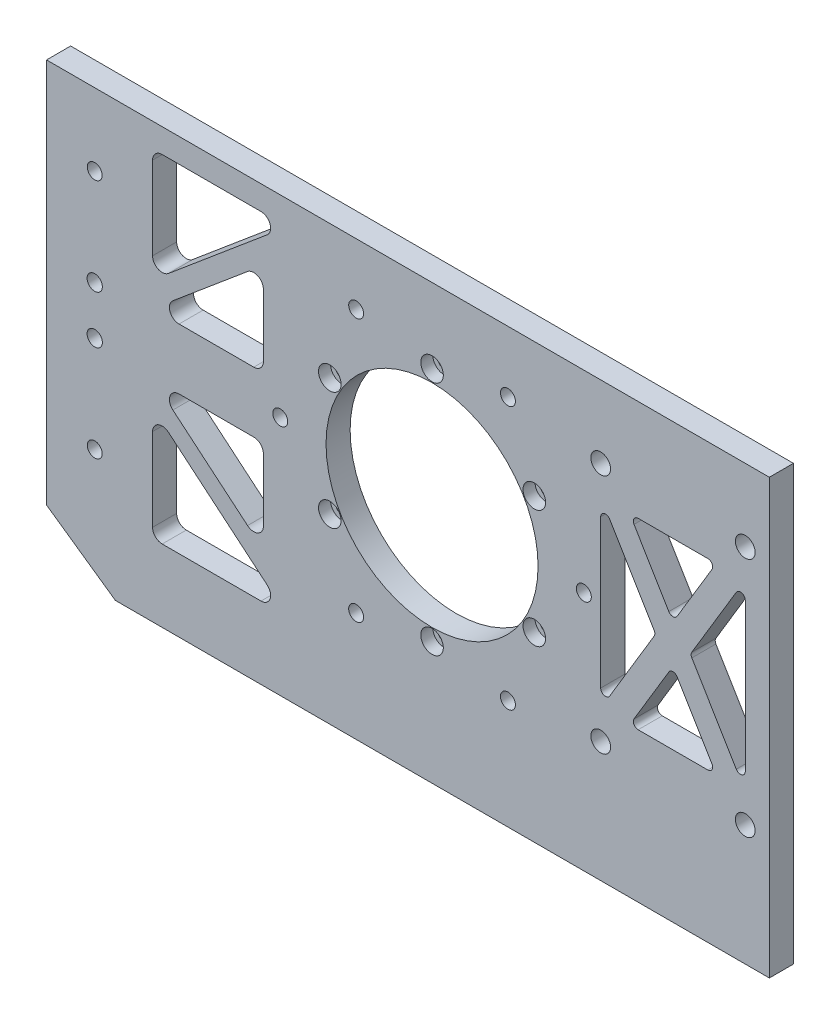
SolidWorks part; units mm, degrees
ref_plane "前视基准面" through (0, 0, 0) normal (0, 0, 1) x (1, 0, 0)
ref_plane "上视基准面" through (0, 0, 0) normal (0, 1, 0) x (1, 0, 0)
ref_plane "右视基准面" through (0, 0, 0) normal (1, 0, 0) x (0, 0, -1)
sketch "草图1" plane through (0, 0, 0) normal (0, 0, 1) x (1, 0, 0)
  line L1 (-80, 40) -> (70, 40)
  line L2 (-80, 40) -> (-80, -40)
  line L3 (-80, -40) -> (70, -40)
  line L4 (70, 40) -> (70, -40)
  circle A0 centre (0, 0) radius 24.5 construction
  circle A1 centre (0, -24.5) radius 1.3
  circle A2 centre (-21.2176, -12.25) radius 1.3
  circle A3 centre (-21.2176, 12.25) radius 1.3
  circle A4 centre (0, 0) radius 22
  circle A5 centre (0, 24.5) radius 1.3
  circle A6 centre (21.2176, 12.25) radius 1.3
  circle A7 centre (21.2176, -12.25) radius 1.3
  point P11 (0, 0)
  point P15 (70, 0)
  dimension "D1" = 49
  dimension "D2" = 2.6
  dimension "D4" = 44
  dimension "D5" = 80
  dimension "D6" = 70
  dimension "D7" = 80
  dimension "D3" = 6
extrude "凸台-拉伸1" add sketch "草图1" along normal blind 5
sketch "草图2" plane through (0, 0, 5) normal (0, 0, 1) x (1, 0, 0)
  circle A0 centre (-21.2176, 12.25) radius 2.34
  circle A1 centre (0, 24.5) radius 2.34
  circle A2 centre (21.2176, 12.25) radius 2.34
  circle A3 centre (21.2176, -12.25) radius 2.34
  circle A4 centre (0, -24.5) radius 2.34
  circle A5 centre (-21.2176, -12.25) radius 2.34
  point P15 (0, 0)
  dimension "D1" = 4.68
  dimension "D2" = 6
extrude "切除-拉伸1" cut sketch "草图2" against normal blind 2.5
sketch "草图3" plane through (0, 0, 5) normal (0, 0, 1) x (1, 0, 0)
  line L0 (0, 0) -> (-70, 0) construction
  line L1 (-70, 0) -> (-70, -25) construction
  line L3 (-70, 0) -> (-70, 24.3133)
  circle A4 centre (-70, -25) radius 1.55
  circle A5 centre (-70, -5) radius 1.5828
  circle A6 centre (-70, 25) radius 1.55
  circle A7 centre (-70, 5) radius 1.5828
  point P6 (-70, 0)
  dimension "D3" = 3.1
  dimension "D4" = 20
  dimension "D1" = 70
  dimension "D2" = 25
extrude "切除-拉伸3" cut sketch "草图3" against normal blind 12.5
sketch "草图4" plane through (0, 0, 5) normal (0, 0, 1) x (1, 0, 0)
  line L0 (-58, 35) -> (-30, 35)
  line L1 (-30, 35) -> (-58, 11.5052)
  line L2 (-58, 11.5052) -> (-58, 35)
  line L3 (-35, 25.5829) -> (-58, 6.2836)
  line L4 (-58, 6.2836) -> (-35, 6.2836)
  line L5 (-35, 6.2836) -> (-35, 25.5829)
  line L8 (70, 40) -> (-80, 40) construction
  line L9 (-80, 40) -> (-80, -40) construction
  dimension "D1" = 5
  dimension "D2" = 22
  dimension "D3" = 140
  dimension "D4" = 45
  dimension "D6" = 4
extrude "切除-拉伸5" cut sketch "草图4" against normal blind 8 contours L2 L0 L1 | L5 L3 L4
fillet "圆角3" radius 2 6 edges at (-35, 6.2836, 2.5) (-58, 6.2836, 2.5) (-35, 25.5829, 2.5) (-30, 35, 2.5) (-58, 11.5052, 2.5) (-58, 35, 2.5)
mirror "镜向2" about plane through (0, 0, 0) normal (0, 1, 0) of "圆角3", "切除-拉伸5"
sketch "草图10" plane through (0, 0, 5) normal (0, 0, 1) x (1, 0, 0)
  line L0 (-80, -40) -> (-127.0531, -7.0531)
  line L1 (-127.0531, -7.0531) -> (-80, 40)
  line L2 (-80, -40) -> (70, -40) construction
  line L3 (-80, 40) -> (-80, -40) construction
  line L4 (-80, 40) -> (-80, -40)
  dimension "D1" = 145
  dimension "D2" = 45
extrude "凸台-拉伸4" add sketch "草图10" against normal up to surface (5 mm away) contours L4 L0 L1 up to face at (-49.3474, 27.3903, 0)
fillet "圆角5" radius 5 1 edges at (-127.0531, -7.0531, 2.5)
sketch "草图11" plane through (0, 0, 5) normal (0, 0, 1) x (1, 0, 0)
  line L0 (0, 0) -> (0, 34) construction
  line L1 (0, 0) -> (-15.75, 27.2798)
  circle A0 centre (0, 0) radius 29 construction
  circle A1 centre (0, 0) radius 34 construction
  circle A2 centre (0, 0) radius 31.5 construction
  circle A3 centre (-15.75, 27.2798) radius 1.55
  circle A4 centre (15.75, 27.2798) radius 1.55
  circle A5 centre (31.5, 0) radius 1.55
  circle A6 centre (15.75, -27.2798) radius 1.55
  circle A7 centre (-15.75, -27.2798) radius 1.55
  circle A8 centre (-31.5, 0) radius 1.55
  point P20 (0, 0)
  dimension "D1" = 58
  dimension "D2" = 68
  dimension "D3" = 63
  dimension "D5" = 3.1
  dimension "D4" = 30
  dimension "D6" = 6
extrude "切除-拉伸7" cut sketch "草图11" against normal blind 25 contours A3 | A4 | A5 | A6 | A7 | A8
sketch "草图12" plane through (0, 0, 5) normal (0, 0, 1) x (1, 0, 0)
  line L0 (0, 0) -> (50, 0) construction
  line L6 (35, -25) -> (65, -25) construction
  line L7 (35, -25) -> (35, 25) construction
  line L8 (35, 25) -> (65, 25) construction
  line L9 (65, -25) -> (65, 25) construction
  line L10 (35, -25) -> (65, 25) construction
  line L11 (35, 25) -> (65, -25) construction
  circle A0 centre (0, 0) radius 28 construction
  circle A1 centre (35, 25) radius 2.05
  circle A2 centre (65, 25) radius 2.05
  circle A3 centre (65, -25) radius 2.05
  circle A4 centre (35, -25) radius 2.05
  dimension "D3" = 56
  dimension "D5" = 4.1
  dimension "D6" = 4.1
  dimension "D1" = 30
  dimension "D2" = 50
  dimension "D4" = 50
extrude "切除-拉伸8" cut sketch "草图12" against normal blind 10
sketch "草图13" plane through (0, 0, 5) normal (0, 0, 1) x (1, 0, 0)
  line L0 (35, 25) -> (65, -25) construction
  line L6 (35, 25) -> (65, -25) construction
  line L10 (35, 19) -> (35, -19)
  line L11 (35, -19) -> (46.4, 0)
  line L12 (46.4, 0) -> (35, 19)
  line L13 (35, -25) -> (65, 25) construction
  line L14 (50, 0) -> (50, -49.4768) construction
  line L15 (65, -19) -> (53.6, 0)
  line L16 (65, 19) -> (65, -19)
  line L17 (53.6, 0) -> (65, 19)
  line L18 (41, 19) -> (50, 4)
  line L19 (50, 4) -> (59, 19)
  line L20 (59, 19) -> (41, 19)
  line L21 (35, 19) -> (65, 19) construction
  line L22 (50, 0) -> (90.4004, 0) construction
  line L23 (50, -4) -> (59, -19)
  line L24 (41, -19) -> (50, -4)
  line L25 (59, -19) -> (41, -19)
  circle A0 centre (35, -25) radius 2.05 construction
  circle A1 centre (65, 25) radius 2.05 construction
  point P4 (50, 0)
  dimension "D1" = 6
  dimension "D2" = 6
  dimension "D3" = 6
  dimension "D4" = 6
  dimension "D5" = 0
extrude "切除-拉伸9" cut sketch "草图13" against normal blind 10
fillet "圆角6" radius 1 12 edges at (35, -19, 2.5) (46.4, 0, 2.5) (35, 19, 2.5) (41, -19, 2.5) (50, -4, 2.5) (59, -19, 2.5) (65, -19, 2.5) (65, 19, 2.5) (53.6, 0, 2.5) (50, 4, 2.5) (59, 19, 2.5) (41, 19, 2.5)
sketch "草图14" plane through (0, 0, 5) normal (0, 0, 1) x (1, 0, 0)
  line L0 (-80, -40) -> (-65.7185, -50)
  line L1 (-65.7185, -50) -> (70, -50)
  line L2 (70, -50) -> (70, -40)
  line L3 (-80, -40) -> (-122.1719, -10.4709) construction
  line L4 (70, -40) -> (70, 40) construction
  line L5 (-80, -40) -> (70, -40) construction
  line L6 (-80, -40) -> (70, -40)
  dimension "D1" = 180
  dimension "D2" = 180
  dimension "D3" = 10
extrude "凸台-拉伸5" add sketch "草图14" against normal up to surface (5 mm away) contours L6 L0 L1 L2 up to face at (50, 13.974, 0)
sketch "草图15" plane through (0, 0, 5) normal (0, 0, 1) x (1, 0, 0)
  line L0 (50, 19) -> (50, -19)
  line L1 (57.2338, 19) -> (42.7662, 19) construction
  line L2 (42.7662, -19) -> (57.2338, -19) construction
  line L3 (50, 0) -> (-80, 0)
  line L4 (-80, 0) -> (-80, 40)
  line L5 (-122.8396, -2.8396) -> (-80, 40) construction
  line L6 (-80, 40) -> (-122.8396, -2.8396)
  line L7 (-80, 0) -> (-80, -40)
  line L8 (-65.7185, -50) -> (-122.1719, -10.4709) construction
  line L9 (-80, -40) -> (-122.1719, -10.4709)
  arc A0 (-122.8396, -2.8396) -> (-122.1719, -10.4709) centre (-119.3041, -6.3751) ccw construction
  arc A1 (-122.8396, -2.8396) -> (-122.1719, -10.4709) centre (-119.3041, -6.3751) ccw
  dimension "D1" = 130
extrude "切除-拉伸10" cut sketch "草图15" against normal blind 10 contours L6 A1 L9 L7 L4
